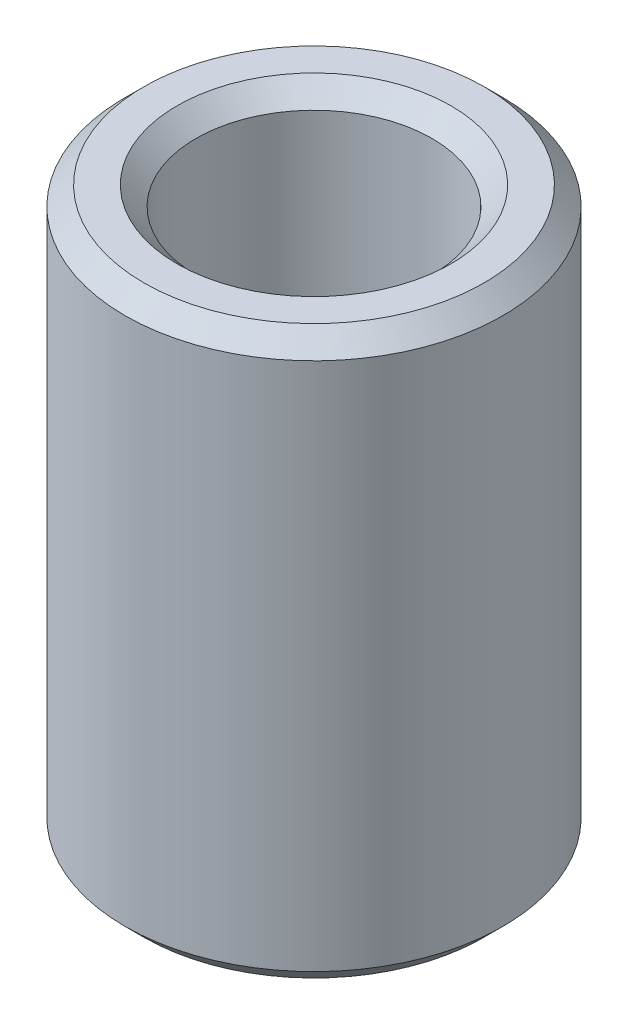
SolidWorks part; units mm, degrees
ref_plane "Ön Düzlem" through (0, 0, 0) normal (0, 0, 1) x (1, 0, 0)
ref_plane "Üst Düzlem" through (0, 0, 0) normal (0, 1, 0) x (1, 0, 0)
ref_plane "Sağ Düzlem" through (0, 0, 0) normal (1, 0, 0) x (0, 0, -1)
sketch "Çizim1" plane through (0, 0, 0) normal (0, 1, 0) x (1, 0, 0)
  circle A0 centre (0, 0) radius 12.5
  circle A1 centre (0, 0) radius 20
  dimension "D1" = 25
  dimension "D2" = 40
extrude "Yükseklik-Ekstrüzyon1" add sketch "Çizim1" along normal blind 60
chamfer "Pah1" distance 2 angle 45 4 edges at (0, 0, 12.5) (0, 0, 20) (0, 60, 12.5) (0, 60, 20)
